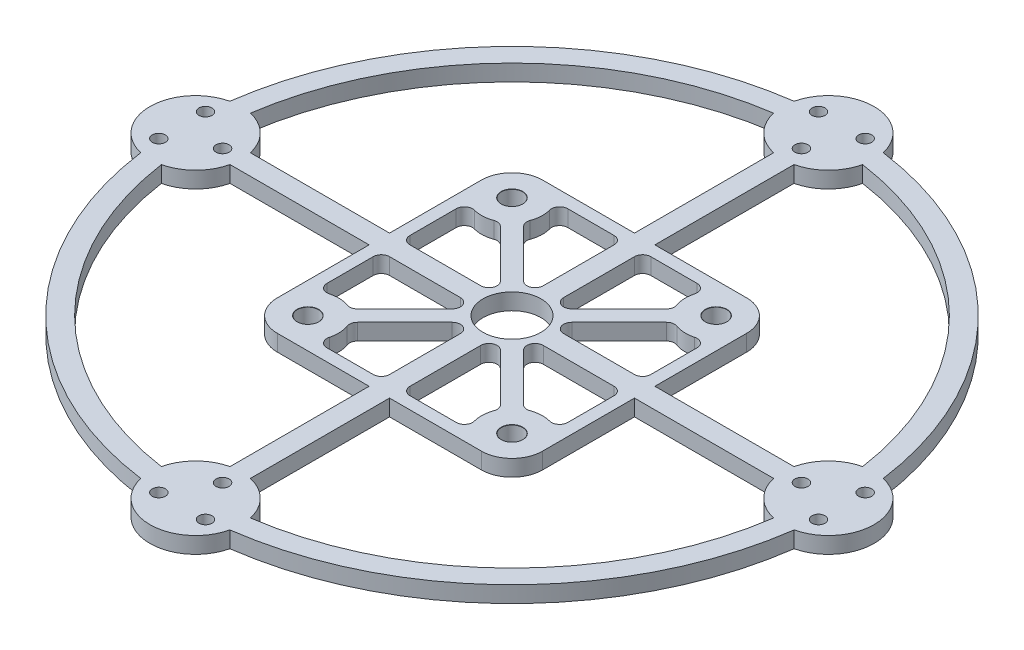
SolidWorks part; units mm, degrees
ref_plane "Front Plane" through (0, 0, 0) normal (0, 0, 1) x (1, 0, 0)
ref_plane "Top Plane" through (0, 0, 0) normal (0, 1, 0) x (1, 0, 0)
ref_plane "Right Plane" through (0, 0, 0) normal (1, 0, 0) x (0, 0, -1)
sketch "Sketch1" plane through (0, 0, 0) normal (0, 1, 0) x (1, 0, 0)
  line L1 (16.25, -16.25) -> (-16.25, -16.25)
  line L2 (16.25, -16.25) -> (16.25, 16.25)
  line L3 (16.25, 16.25) -> (-16.25, 16.25)
  line L4 (-16.25, -16.25) -> (-16.25, 16.25)
  line L5 (16.25, -16.25) -> (-16.25, 16.25) construction
  line L6 (16.25, 16.25) -> (-16.25, -16.25) construction
  point P0 (0, 0)
  dimension "D1" = 32.5
extrude "Boss-Extrude1" add sketch "Sketch1" along normal mid plane 2
sketch "Sketch5" plane through (0, 1, 0) normal (0, 1, 0) x (1, 0, 0)
  line L1 (12.5, -12.5) -> (-12.5, -12.5) construction
  line L2 (12.5, -12.5) -> (12.5, 12.5) construction
  line L3 (12.5, 12.5) -> (-12.5, 12.5) construction
  line L4 (-12.5, -12.5) -> (-12.5, 12.5) construction
  line L5 (12.5, -12.5) -> (-12.5, 12.5) construction
  line L6 (12.5, 12.5) -> (-12.5, -12.5) construction
  point P0 (0, 0)
  point P1 (-12.5, 12.5)
  point P2 (12.5, -12.5)
  point P3 (12.5, 12.5)
  point P4 (-12.5, -12.5)
  dimension "D1" = 25
hole_wizard "M2 Clearance Hole1" positions "Sketch5" profile "Sketch6" hole size "M2" standard "ISO"
sketch "Sketch6" plane through (-12.5, 1, 12.5) normal (1, 0, 0) x (0, 0, 1)
  line L0 (0, 0) -> (0, 2)
  line L1 (0, 2) -> (1.3, 2)
  line L2 (1.3, 2) -> (1.3, 0.025)
  line L3 (1.3, 0.025) -> (1.325, 0)
  line L5 (1.325, 0) -> (0, 0)
  line L6 (-1.3, 0.025) -> (-1.325, 0) construction
  line L11 (0, -6.35) -> (0, 107.95) construction
  dimension "Thru Hole Dia." = 2.6
  dimension "Thru Hole Depth" = 2
  dimension "Near C'Sink Dia." = 2.65
  dimension "Near C'Sink Angle" = 90
sketch "Sketch7" plane through (0, -1, 0) normal (0, -1, 0) x (1, 0, 0)
  line L0 (16.25, 16.25) -> (16.25, -16.25) construction
  line L1 (0, 0) -> (38.75, 0) construction
  line L2 (38.75, 0) -> (40.4, 2.8579) construction
  line L3 (38.75, 0) -> (35.45, 0) construction
  line L4 (38.75, 0) -> (40.4, -2.8579) construction
  line L5 (33.2913, 1.25) -> (16.25, 1.25)
  line L6 (16.25, 1.25) -> (16.25, -1.25)
  line L7 (16.25, 12.5) -> (16.25, -12.5)
  line L9 (16.25, -1.25) -> (33.2913, -1.25)
  circle A0 centre (38.75, 0) radius 22.5 construction
  circle A1 centre (38.75, 0) radius 3.3 construction
  circle A3 centre (35.45, 0) radius 0.8
  circle A5 centre (38.75, 0) radius 4.1 construction
  circle A6 centre (38.75, 0) radius 5.6
  circle A7 centre (40.4, 2.8579) radius 0.8
  circle A8 centre (40.4, -2.8579) radius 0.8
  dimension "D1" = 45
  dimension "D2" = 6.6
  dimension "D5" = 1.6
  dimension "D3" = 120
  dimension "D4" = 120
  dimension "D7" = 2.5
  dimension "D6" = 1.5
  dimension "D8" = 3
extrude "Boss-Extrude2" add sketch "Sketch7" against normal up to surface (2 mm away)
sketch "Sketch8" plane through (0, 0, 0) normal (0, 0, 1) x (1, 0, 0)
  line L0 (0, 0) -> (0, -50000) construction
pattern_circular "CirPattern1" count 4 every 90 about axis through (0, 0, 0) along (0, 1, 0) of "Boss-Extrude2"
sketch "Sketch13" plane through (0, -1, 0) normal (0, -1, 0) x (1, 0, 0)
  line L0 (0, -38.75) -> (-5.6, -38.75) construction
  arc A0 (-5.4559, -37.4877) -> (-37.4877, -5.4559) centre (0, 0) cw
  arc A1 (-1.25, -33.2913) -> (1.25, -33.2913) centre (0, -38.75) ccw construction
  arc A2 (-33.2913, 1.25) -> (-33.2913, -1.25) centre (-38.75, 0) ccw construction
  arc A3 (-40.0123, -5.4559) -> (-5.4559, -40.0123) centre (0, 0) ccw
  arc A4 (-5.4559, -40.0123) -> (-5.4559, -37.4877) centre (0, -38.75) cw
  arc A5 (-40.0123, -5.4559) -> (-37.4877, -5.4559) centre (-38.75, 0) ccw
  point P1 (0, 0)
  point P12 (-33, -4.5028)
  dimension "D1" = 2.5
extrude "Boss-Extrude3" add sketch "Sketch13" against normal up to surface (2 mm away) up to face at (-12.5, 1, -11.175)
pattern_circular "CirPattern3" count 4 every 90 about axis through (0, 0, 0) along (0, -1, 0) of "Boss-Extrude3"
sketch "Sketch14" plane through (0, 1, 0) normal (0, 1, 0) x (1, 0, 0)
  line L0 (-16.25, -1.25) -> (-16.25, -16.25) construction
  line L4 (-12.5, -12.5) -> (0, 0) construction
  line L5 (-14.75, -1.25) -> (-14.75, -9.5)
  line L6 (-14.75, -14.75) -> (-1.25, -14.75)
  line L7 (-14.75, -1.25) -> (-14.75, -14.75)
  line L8 (-14.75, -14.75) -> (-1.25, -14.75) construction
  line L9 (-14.75, -1.25) -> (-14.75, -14.75) construction
  line L10 (-11.7929, -13.2071) -> (0.7071, -0.7071) construction
  line L11 (-13.2071, -11.7929) -> (-0.7071, 0.7071) construction
  line L12 (-14.75, -1.25) -> (-2.6642, -1.25)
  line L13 (-2.6642, -1.25) -> (-10.6515, -9.2373)
  line L14 (-1.25, -14.75) -> (-1.25, -2.6642)
  line L15 (-1.25, -2.6642) -> (-9.2373, -10.6515)
  line L16 (-1.25, -14.75) -> (-9.5, -14.75)
  circle A0 centre (-12.5, -12.5) radius 3.75 construction
  arc A2 (-14.75, -9.5) -> (-10.6515, -9.2373) centre (-12.5, -12.5) cw
  arc A3 (-9.2373, -10.6515) -> (-9.5, -14.75) centre (-12.5, -12.5) cw
  point P21 (0, 0)
  dimension "D1" = 1.5
  dimension "D2" = 1
  dimension "D3" = 1
extrude "Cut-Extrude2" cut sketch "Sketch14" against normal through all both and the other way through all
pattern_circular "CirPattern4" count 4 every 90 about axis through (0, 0, 0) along (0, 1, 0) of "Cut-Extrude2"
fillet "Fillet2" radius 1 32 edges at (1.25, 0, 14.75) (1.25, 0, 2.6642) (14.75, 0, 1.25) (2.6642, 0, 1.25) (14.75, 0, -1.25) (1.25, 0, -2.6642) (2.6642, 0, -1.25) (1.25, 0, -14.75) (-2.6642, 0, -1.25) (-1.25, 0, 14.75) (-14.75, 0, 1.25) (-1.25, 0, 2.6642) (-2.6642, 0, 1.25) (-1.25, 0, -14.75) (-14.75, 0, -1.25) (-1.25, 0, -2.6642)
sketch "Sketch15" plane through (0, 1, 0) normal (0, 1, 0) x (1, 0, 0)
  circle A0 centre (0, 0) radius 4.5545 construction
  arc A1 (-2.9571, 4.3713) -> (-1.25, 5.0784) centre (-2.25, 5.0784) ccw construction
  circle A2 centre (0, 0) radius 3.5545
  dimension "D1" = 1
extrude "Cut-Extrude3" cut sketch "Sketch15" against normal through all both and the other way through all
fillet "Fillet1" radius 3.75 4 edges at (-16.25, 0, -16.25) (16.25, 0, -16.25) (16.25, 0, 16.25) (-16.25, 0, 16.25)
